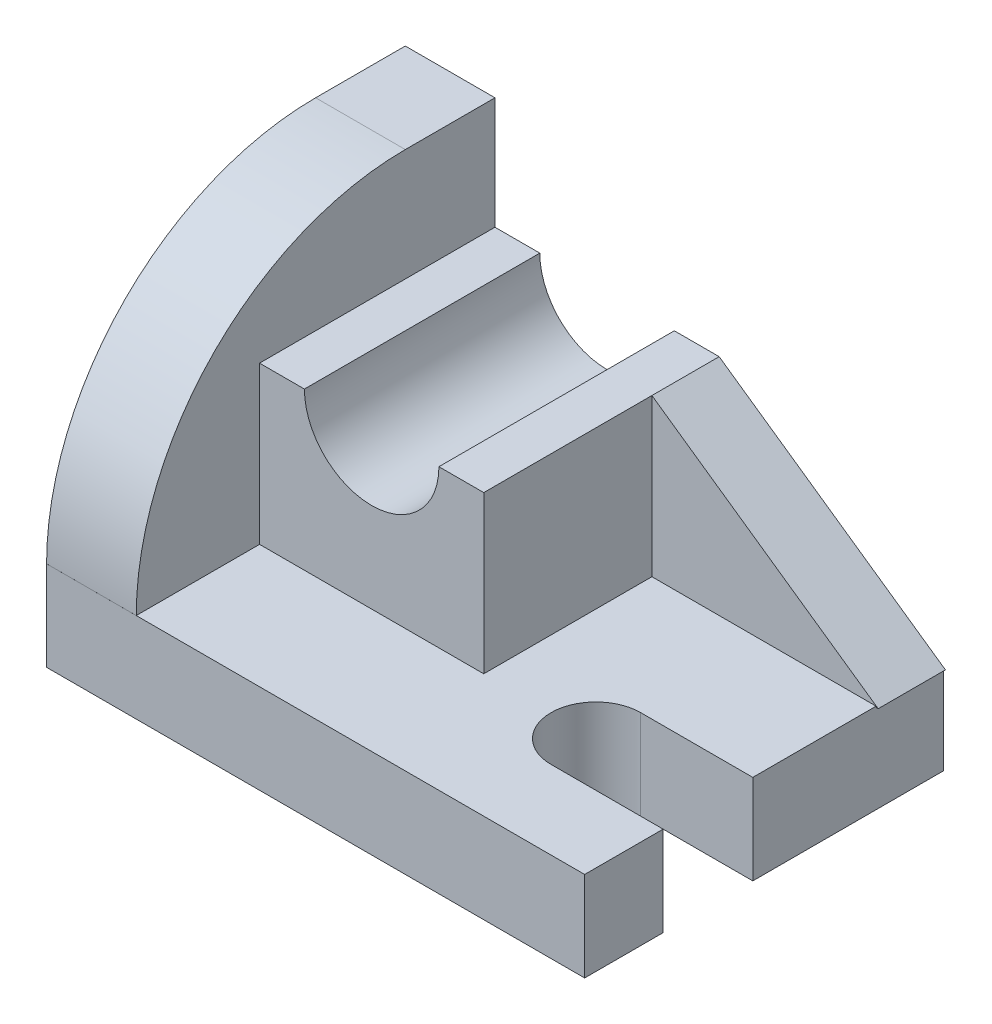
SolidWorks part; units mm, degrees
ref_plane "Front Plane" through (0, 0, 0) normal (0, 0, 1) x (1, 0, 0)
ref_plane "Top Plane" through (0, 0, 0) normal (0, 1, 0) x (1, 0, 0)
ref_plane "Right Plane" through (0, 0, 0) normal (1, 0, 0) x (0, 0, -1)
sketch "Sketch1" plane through (0, 0, 0) normal (0, 1, 0) x (1, 0, 0)
  line L1 (-48, 32) -> (48, 32)
  line L2 (-48, 32) -> (-48, -32)
  line L3 (-48, -32) -> (48, -32)
  line L4 (48, 32) -> (48, -32)
  line L5 (-48, 32) -> (48, -32) construction
  line L6 (-48, -32) -> (48, 32) construction
  point P0 (0, 0)
  dimension "D1" = 96
  dimension "D2" = 64
extrude "Boss-Extrude1" add sketch "Sketch1" along normal blind 16
sketch "Sketch2" plane through (0, 16, 0) normal (0, 1, 0) x (1, 0, 0)
  line L0 (48, -10) -> (28, -10) construction
  line L1 (48, -32) -> (48, 32) construction
  line L2 (48, -18) -> (28, -18)
  line L3 (48, -2) -> (28, -2)
  line L4 (-48, -32) -> (48, -32) construction
  arc A0 (48, -18) -> (48, -2) centre (48, -10) ccw
  arc A1 (28, -2) -> (28, -18) centre (28, -10) ccw
  point P4 (38, -10)
  dimension "D1" = 8
  dimension "D2" = 20
  dimension "D3" = 22
extrude "Cut-Extrude2" cut sketch "Sketch2" against normal blind 16
sketch "Sketch3" plane through (0, 0, 32) normal (0, 0, 1) x (1, 0, 0)
  line L0 (-48, 16) -> (48, 16) construction
  line L2 (-32, 16) -> (8, 16)
  line L3 (-32, 16) -> (-32, 44)
  line L4 (-32, 44) -> (8, 44)
  line L5 (8, 16) -> (8, 44)
  circle A0 centre (-12, 44) radius 12
  line M8 (48, 16) -> (-48, 16)
  dimension "D1" = 40
  dimension "D2" = 28
  dimension "D3" = 16
extrude "Boss-Extrude2" add sketch "Sketch3" against normal blind 42 from offset 22 contours A0 L4 L3 L5 M8 offset against normal yes
sketch "Sketch5" plane through (-48, 0, 0) normal (-1, 0, 0) x (0, 0, 1)
  line L1 (-32, 0) -> (31.9971, 0)
  line L2 (-32, 0) -> (-32, 64)
  line L3 (-32, 64) -> (-16.0029, 64)
  line L4 (31.9971, 0) -> (31.9971, 16)
  arc A0 (31.9971, 16) -> (-16.0029, 64) centre (-16.0029, 16) ccw
  point P7 (31.9971, 64)
  dimension "D3" = 48
  dimension "D1" = 63.9971
  dimension "D2" = 64
extrude "Boss-Extrude3" add sketch "Sketch5" against normal blind 16
sketch "Sketch6" plane through (0, 0, -32) normal (0, 0, -1) x (-1, 0, 0)
  line L0 (-8, 44) -> (-48.3682, 15.792)
  line L1 (-48.3682, 15.792) -> (-8, 16)
  line L2 (-8, 16) -> (-8, 44)
extrude "Boss-Extrude4" add sketch "Sketch6" against normal blind 12
